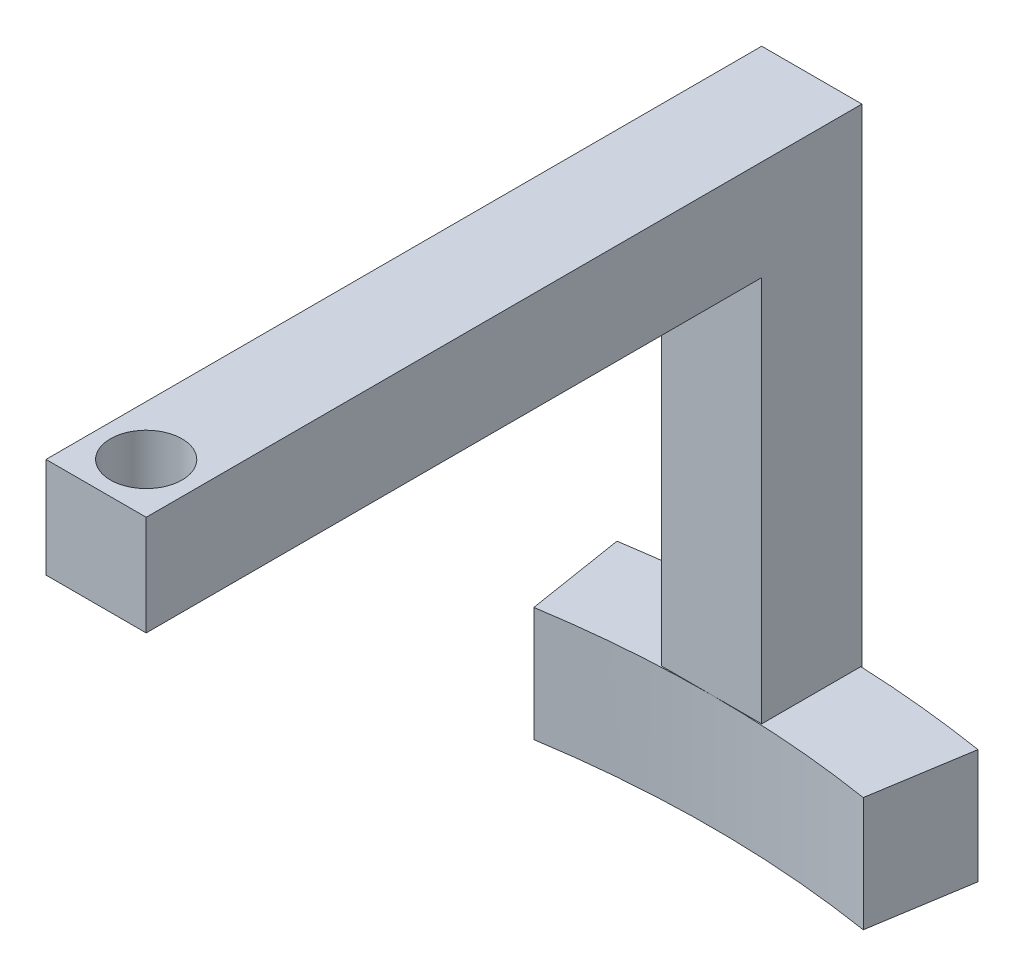
SolidWorks part; units mm, degrees
ref_plane "Front Plane" through (0, 0, 0) normal (0, 0, 1) x (1, 0, 0)
ref_plane "Top Plane" through (0, 0, 0) normal (0, 1, 0) x (1, 0, 0)
ref_plane "Right Plane" through (0, 0, 0) normal (1, 0, 0) x (0, 0, -1)
sketch "Sketch1" plane through (0, 0, 0) normal (1, 0, 0) x (0, 0, -1)
  line L0 (0, 30.375) -> (25, 30.375)
  line L1 (25, 30.375) -> (25, 9.375)
  line L2 (25, 9.375) -> (21.5, 9.375)
  line L3 (21.5, 9.375) -> (21.5, 26.875)
  line L4 (21.5, 26.875) -> (0, 26.875)
  line L5 (0, 26.875) -> (0, 30.375)
  dimension "D1" = 3.5
  dimension "D2" = 3.5
  dimension "D3" = 21
  dimension "D4" = 25
extrude "Boss-Extrude1" add sketch "Sketch1" along normal blind 3.5
sketch "Sketch3" plane through (0, 9.375, 0) normal (0, -1, 0) x (-1, 0, 0)
  line L0 (-3.5, 25) -> (0, 25) construction
  line L1 (4.5548, 24.5) -> (4.0031, 21.0438)
  line L2 (-7.5031, 21.0438) -> (-8.0548, 24.5)
  arc A0 (4.5548, 24.5) -> (-8.0548, 24.5) centre (-1.75, -15) ccw
  arc A1 (4.0031, 21.0438) -> (-7.5031, 21.0438) centre (-1.75, -15) ccw
  point P3 (-1.75, 25)
  point P6 (-1.75, 25)
  dimension "D1" = 0.5
  dimension "D2" = 3.5
  dimension "D3" = 40
extrude "Boss-Extrude3" add sketch "Sketch3" against normal blind 4
sketch "Sketch4" plane through (0, 30.375, 0) normal (0, 1, 0) x (1, 0, 0)
  line L0 (3.5, 0) -> (0, 0) construction
  line L1 (3.5, 25) -> (3.5, 0) construction
  circle A0 centre (1.75, 1.75) radius 1.25
  dimension "D1" = 2.5
  dimension "D2" = 1.75
  dimension "D3" = 1.75
extrude "Cut-Extrude1" cut sketch "Sketch4" against normal blind 4
